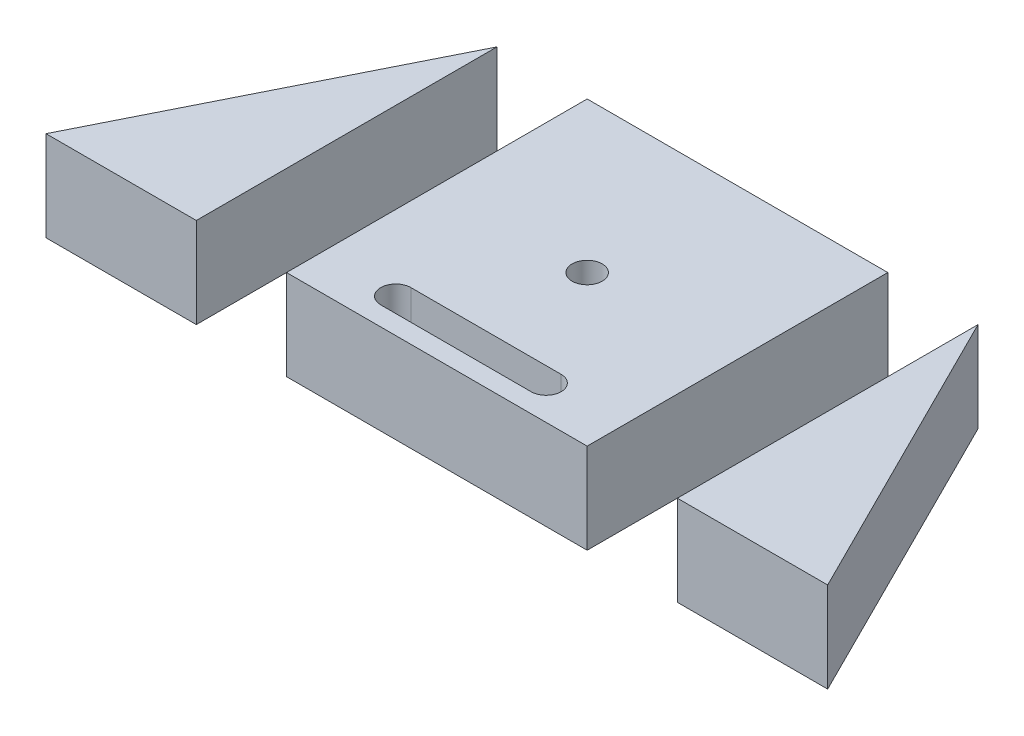
SolidWorks part; units mm, degrees
ref_plane "前视基准面" through (0, 0, 0) normal (0, 0, 1) x (1, 0, 0)
ref_plane "上视基准面" through (0, 0, 0) normal (0, 1, 0) x (1, 0, 0)
ref_plane "右视基准面" through (0, 0, 0) normal (1, 0, 0) x (0, 0, -1)
other "Configuration Table"
sketch "草图1" plane through (0, 0, 0) normal (0, 1, 0) x (1, 0, 0)
  line L0 (80, -50) -> (130, -50)
  line L1 (-50, 50) -> (50, 50)
  line L2 (-50, 50) -> (-50, -50)
  line L3 (-50, -50) -> (50, -50)
  line L4 (50, 50) -> (50, -50)
  line L5 (-50, 50) -> (50, -50) construction
  line L6 (-50, -50) -> (50, 50) construction
  line L7 (130, -50) -> (80, 50)
  line L8 (80, 50) -> (80, -50)
  point P0 (0, 0)
  dimension "D1" = 100
  dimension "D2" = 100
  dimension "D3" = 100
  dimension "D4" = 30
  dimension "D5" = 50
extrude "凸台-拉伸1" add sketch "草图1" along normal blind 30
mirror "镜向1" about plane through (0, 0, 0) normal (1, 0, 0) of bodies 107
sketch "草图2" plane through (0, 30, 0) normal (0, 1, 0) x (1, 0, 0)
  line L0 (-25, -38.6493) -> (25, -38.6493) construction
  line L1 (-25, -33.6493) -> (25, -33.6493)
  line L2 (-25, -43.6493) -> (25, -43.6493)
  line L3 (0, 0) -> (0, -38.6493) construction
  arc A0 (-25, -33.6493) -> (-25, -43.6493) centre (-25, -38.6493) ccw
  arc A1 (25, -43.6493) -> (25, -33.6493) centre (25, -38.6493) ccw
  circle A2 centre (0, 0) radius 5
  point P2 (0, -38.6493)
  dimension "D3" = 10
  dimension "D1" = 10
  dimension "D2" = 50
extrude "切除-拉伸1" cut sketch "草图2" against normal blind 10
